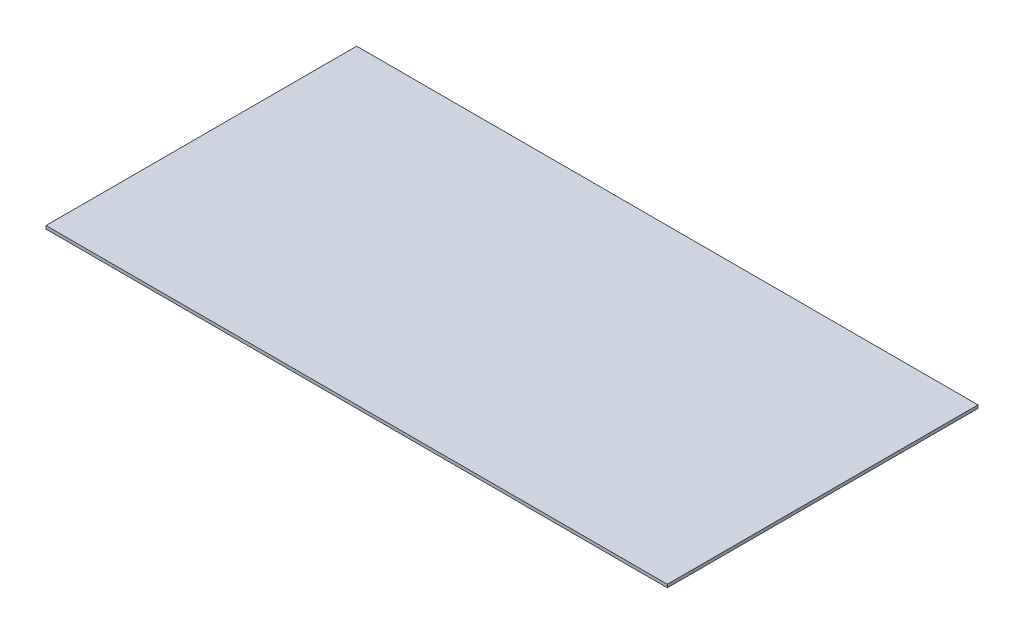
SolidWorks part; units mm, degrees
ref_plane "Front Plane" through (0, 0, 0) normal (0, 0, 1) x (1, 0, 0)
ref_plane "Top Plane" through (0, 0, 0) normal (0, 1, 0) x (1, 0, 0)
ref_plane "Right Plane" through (0, 0, 0) normal (1, 0, 0) x (0, 0, -1)
sketch "Sketch1" plane through (0, 0, 0) normal (0, 1, 0) x (1, 0, 0)
  line L1 (-20, 10) -> (20, 10)
  line L2 (-20, 10) -> (-20, -10)
  line L3 (-20, -10) -> (20, -10)
  line L4 (20, 10) -> (20, -10)
  line L5 (-20, 10) -> (20, -10) construction
  line L6 (-20, -10) -> (20, 10) construction
  point P0 (0, 0)
  dimension "D1" = 20
  dimension "D2" = 40
extrude "Boss-Extrude1" add sketch "Sketch1" along normal blind 0.2
